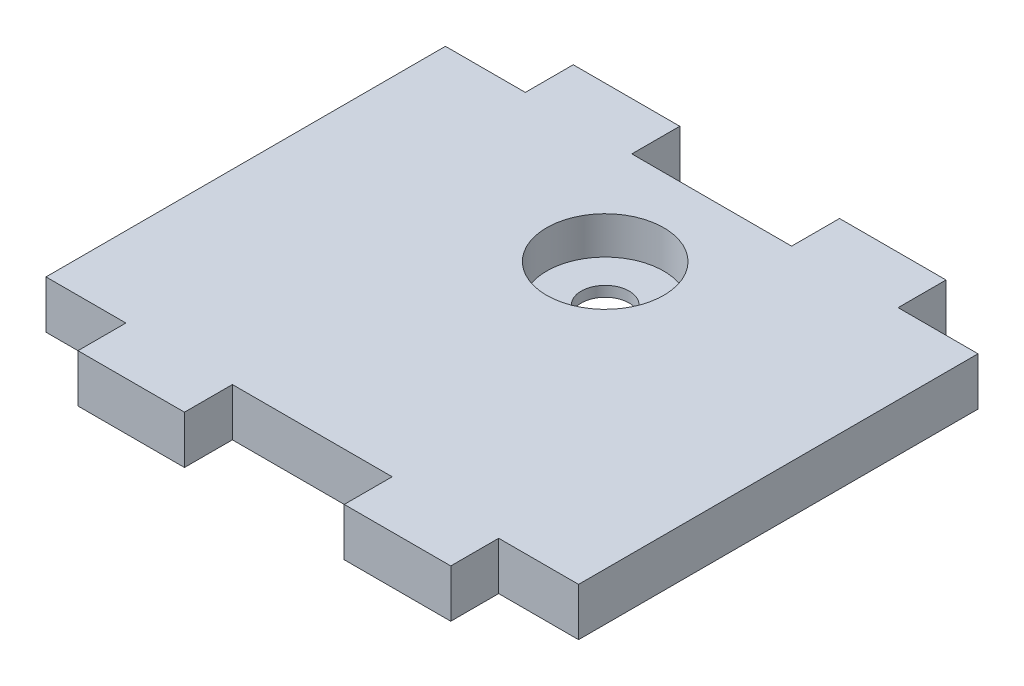
SolidWorks part; units mm, degrees
ref_plane "Front Plane" through (0, 0, 0) normal (0, 0, 1) x (1, 0, 0)
ref_plane "Top Plane" through (0, 0, 0) normal (0, 1, 0) x (1, 0, 0)
ref_plane "Right Plane" through (0, 0, 0) normal (1, 0, 0) x (0, 0, -1)
sketch "Sketch2" plane through (0, 0, 0) normal (0, 1, 0) x (1, 0, 0)
  line L0 (0, 37.5) -> (0, -37.5) construction
  line L1 (-50, 37.5) -> (50, 37.5)
  line L2 (-50, 37.5) -> (-50, -37.5)
  line L3 (-50, -37.5) -> (50, -37.5)
  line L4 (50, 37.5) -> (50, -37.5)
  line L5 (-50, 37.5) -> (50, -37.5) construction
  line L6 (-50, -37.5) -> (50, 37.5) construction
  line L7 (15, 37.5) -> (15, 46.5)
  line L8 (-35, 37.5) -> (-15, 37.5)
  line L9 (-35, 37.5) -> (-35, 46.5)
  line L10 (-35, 46.5) -> (-15, 46.5)
  line L11 (-15, 37.5) -> (-15, 46.5)
  line L12 (35, 46.5) -> (15, 46.5)
  line L13 (35, 37.5) -> (35, 46.5)
  line L14 (35, 37.5) -> (15, 37.5)
  line L15 (-29, 17.5) -> (29, 17.5)
  line L16 (-50, 0) -> (50, 0) construction
  line L17 (35, -37.5) -> (15, -37.5)
  line L18 (35, -37.5) -> (35, -46.5)
  line L19 (35, -46.5) -> (15, -46.5)
  line L20 (-15, -37.5) -> (-15, -46.5)
  line L21 (-35, -46.5) -> (-15, -46.5)
  line L22 (-35, -37.5) -> (-35, -46.5)
  line L23 (-35, -37.5) -> (-15, -37.5)
  line L24 (15, -37.5) -> (15, -46.5)
  circle A0 centre (-29, 17.5) radius 4
  circle A1 centre (29, 17.5) radius 4
  circle A2 centre (0, 17.5) radius 4.5
  point P0 (0, 0)
  point P20 (0, 17.5)
  dimension "D3" = 8
  dimension "D9" = 9
  dimension "D1" = 75
  dimension "D2" = 100
  dimension "D4" = 20
  dimension "D5" = 21
  dimension "D6" = 20
  dimension "D7" = 9
  dimension "D8" = 15
extrude "Boss-Extrude1" add sketch "Sketch2" along normal blind 9
sketch "Sketch3" plane through (0, 9, 0) normal (0, 1, 0) x (1, 0, 0)
  circle A0 centre (0, 17.5) radius 11
  dimension "D1" = 22
extrude "Cut-Extrude1" cut sketch "Sketch3" against normal blind 7.05
